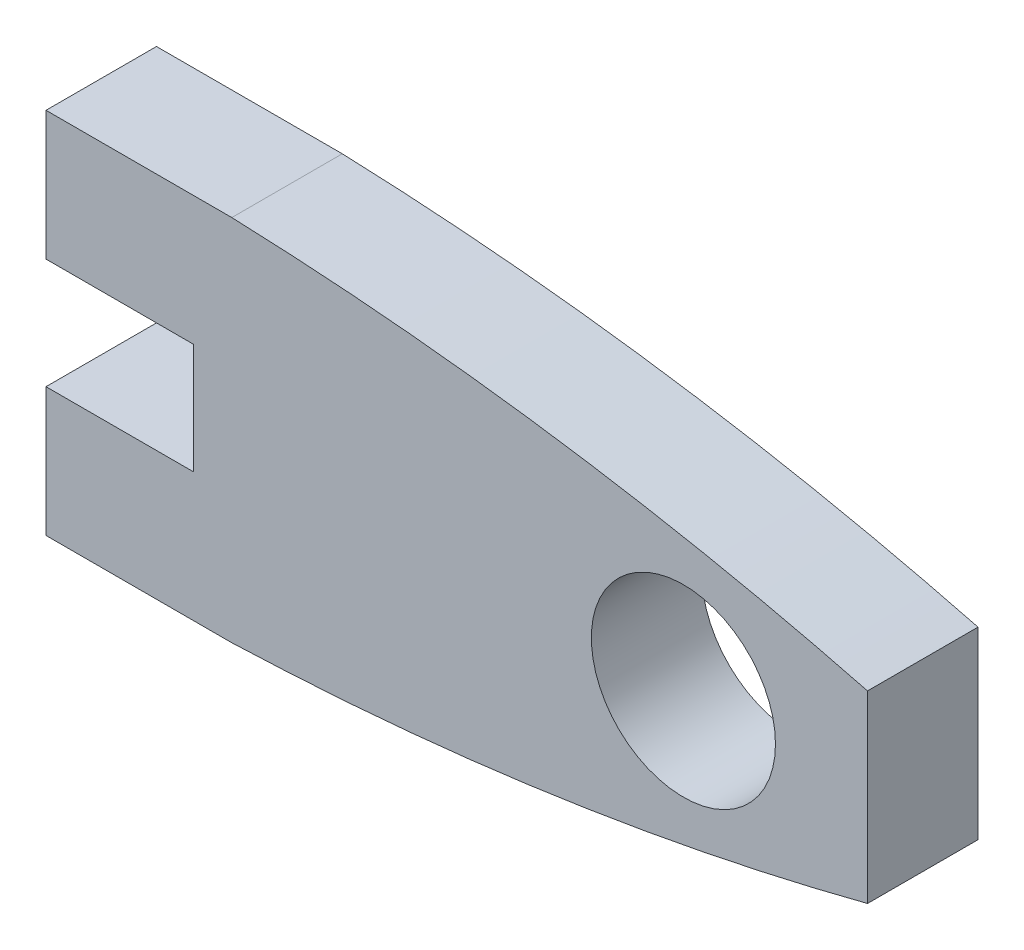
SolidWorks part; units mm, degrees
ref_plane "Front Plane" through (0, 0, 0) normal (0, 0, 1) x (1, 0, 0)
ref_plane "Top Plane" through (0, 0, 0) normal (0, 1, 0) x (1, 0, 0)
ref_plane "Right Plane" through (0, 0, 0) normal (1, 0, 0) x (0, 0, -1)
sketch "Sketch1" plane through (0, 0, 0) normal (0, 0, 1) x (1, 0, 0)
  line L0 (-14.0809, 0) -> (19.5956, 0) construction
  line L1 (-11.6544, -2.5) -> (-11.6544, -5)
  line L2 (-11.6544, 5) -> (-5.6088, 5)
  line L3 (-11.6544, 5) -> (-11.6544, 2.5)
  line L4 (-11.6544, -5) -> (-5.6088, -5)
  line L5 (11.6544, 2.5) -> (11.6544, -2.5)
  line L6 (-11.6544, 5) -> (11.6544, -5) construction
  line L7 (-11.6544, -5) -> (11.6544, 5) construction
  line L8 (-11.6544, 2.5) -> (-6.6544, 2.5)
  line L10 (-11.6544, -2.5) -> (-6.6544, -2.5)
  line L11 (-6.6544, 2.5) -> (-6.6544, -2.5)
  line L12 (-16.6544, 2.5) -> (-6.6544, -2.5) construction
  line L13 (-16.6544, -2.5) -> (-6.6544, 2.5) construction
  circle A0 centre (6.6544, 0) radius 2.5
  spline S0 degree 2 poles (-11.6544, 5) (0.3499, 5.4249) (11.6544, 2.5) knots 0 0 0 0.737931 0.737931 0.737931
  spline S1 degree 2 poles (-11.6544, -5) (0.3499, -5.4249) (11.6544, -2.5) knots 0 0 0 0.737931 0.737931 0.737931
  point P3 (0, 0)
  point P8 (-11.6544, 0)
  dimension "D4" = 5
  dimension "D1" = 10
  dimension "D2" = 5
  dimension "D3" = 10
  dimension "D5" = 5
extrude "Boss-Extrude1" add sketch "Sketch1" along normal blind 3 contours L4 S1 L5 S0 L2 L3 L8 L11 L10 L1 A0
sketch "Sketch2" plane through (0, 0, 3) normal (0, 0, 1) x (1, 0, 0)
  line L0 (-6.6544, 2.5) -> (-6.6544, -2.5) construction
  line L1 (-11.6544, 2.5) -> (-6.6544, 2.5)
  line L2 (-11.6544, 2.5) -> (-11.6544, 1.5)
  line L3 (-11.6544, 1.5) -> (-6.6544, 1.5)
  line L4 (-6.6544, 2.5) -> (-6.6544, 1.5)
  line L6 (-11.6544, -2.5) -> (-6.6544, -2.5)
  line L7 (-11.6544, -2.5) -> (-11.6544, -1.5)
  line L8 (-11.6544, -1.5) -> (-6.6544, -1.5)
  line L9 (-6.6544, -2.5) -> (-6.6544, -1.5)
  dimension "D1" = 1
  dimension "D2" = 1
extrude "Boss-Extrude2" add sketch "Sketch2" against normal blind 3
sketch "Sketch3" plane through (0, 0, 3) normal (0, 0, 1) x (1, 0, 0)
  line L0 (-11.6544, 1.5) -> (-6.6544, 1.5) construction
  line L1 (-11.6544, -5) -> (-5.6088, -5) construction
  line L2 (-11.6544, 5) -> (-10.6544, 5)
  line L3 (-11.6544, 5) -> (-11.6544, 1.5)
  line L4 (-11.6544, 1.5) -> (-10.6544, 1.5)
  line L5 (-10.6544, 5) -> (-10.6544, 1.5)
  line L6 (-11.6544, -1.5) -> (-10.6544, -1.5)
  line L7 (-11.6544, -1.5) -> (-11.6544, -5)
  line L8 (-11.6544, -5) -> (-10.6544, -5)
  line L9 (-10.6544, -1.5) -> (-10.6544, -5)
  dimension "D1" = 1
  dimension "D2" = 1
extrude "Cut-Extrude1" cut sketch "Sketch3" against normal up to next
